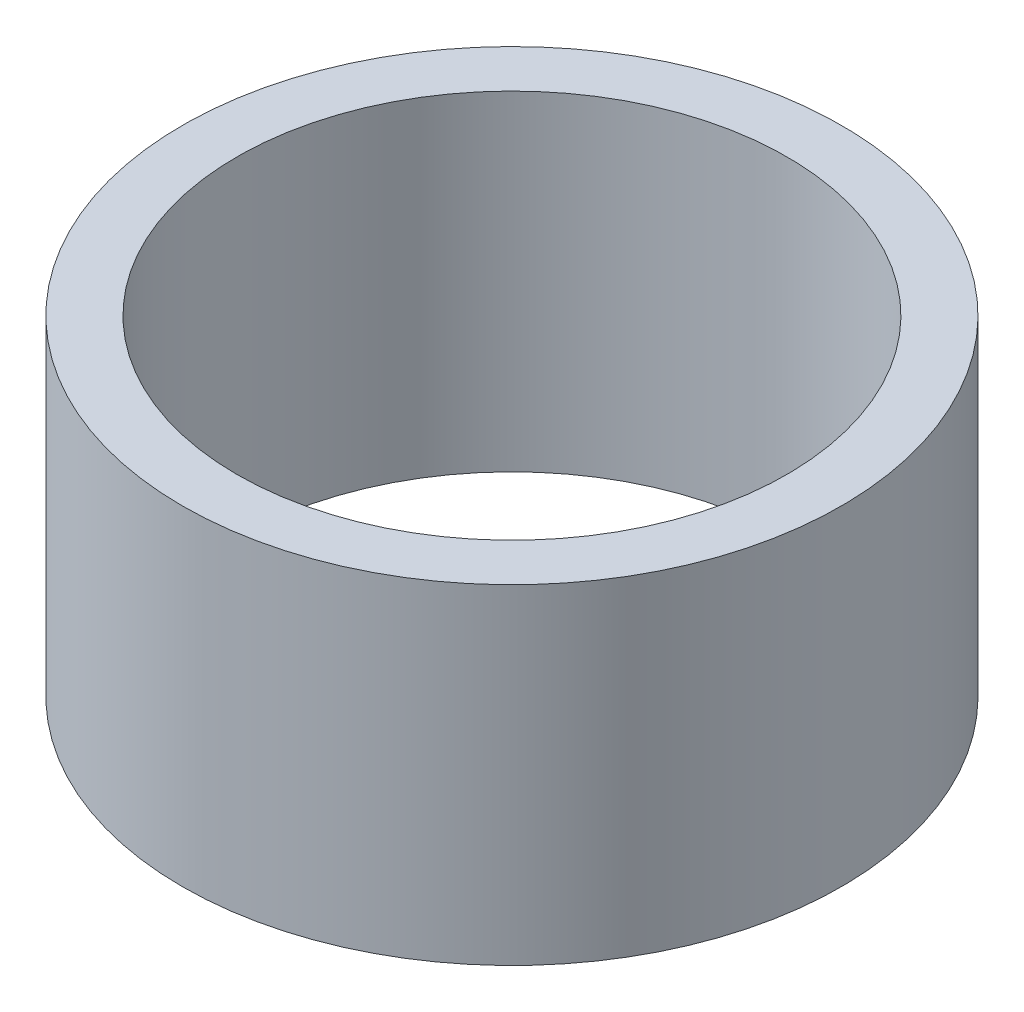
SolidWorks part; units mm, degrees
ref_plane "Front Plane" through (0, 0, 0) normal (0, 0, 1) x (1, 0, 0)
ref_plane "Top Plane" through (0, 0, 0) normal (0, 1, 0) x (1, 0, 0)
ref_plane "Right Plane" through (0, 0, 0) normal (1, 0, 0) x (0, 0, -1)
sketch "Sketch1" plane through (0, 0, 0) normal (0, 1, 0) x (1, 0, 0)
  circle A0 centre (0, 0) radius 152.3079
extrude "Boss-Extrude1" add sketch "Sketch1" along normal blind 152.4
sketch "Sketch2" plane through (0, 152.4, 0) normal (0, 1, 0) x (1, 0, 0)
  circle A0 centre (0, 0) radius 127.1206
extrude "Cut-Extrude1" cut sketch "Sketch2" against normal blind 152.4
